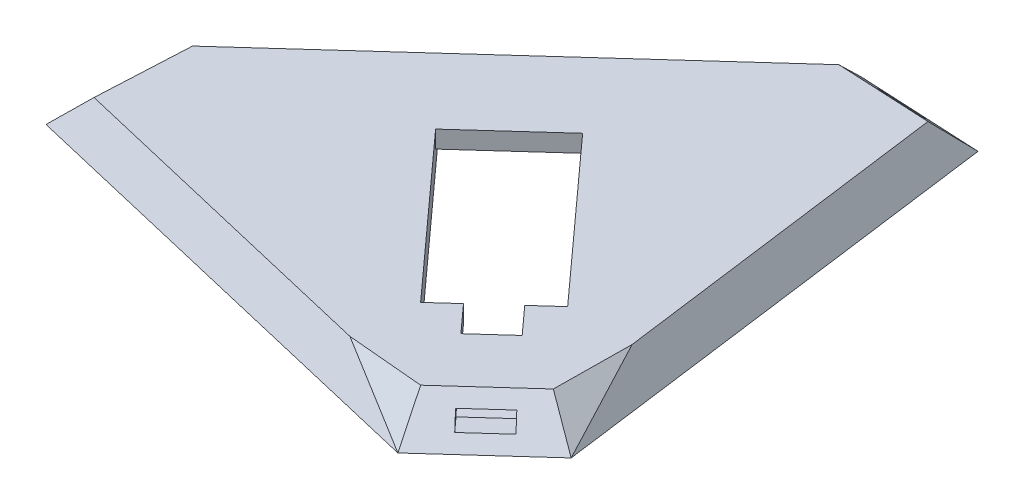
SolidWorks part; units mm, degrees
ref_plane "Front Plane" through (0, 0, 0) normal (0, 0, 1) x (1, 0, 0)
ref_plane "Top Plane" through (0, 0, 0) normal (0, 1, 0) x (1, 0, 0)
ref_plane "Right Plane" through (0, 0, 0) normal (1, 0, 0) x (0, 0, -1)
sketch "Sketch1" plane through (0, 0, 0) normal (0, 1, 0) x (1, 0, 0)
  line L20 (52.4944, -151.1339) -> (51.789, -165.2584)
  line L21 (51.789, -165.2584) -> (104.862, -177.7702)
  line L22 (104.862, -177.7702) -> (115.3483, -168.2814)
  line L23 (115.3483, -168.2814) -> (108.1862, -114.226)
  line L24 (108.1862, -114.226) -> (94.0617, -113.5206)
  line L25 (94.0617, -113.5206) -> (52.4944, -151.1339)
  line L26 (52.4944, -151.1339) -> (51.789, -165.2584) construction
  line L27 (108.1862, -114.226) -> (94.0617, -113.5206) construction
extrude "Boss-Extrude1" add sketch "Sketch1" along normal up to vertex (4 mm away)
draft "Draft1" type of draft neutral plane draft angle 45 faces to draft 4 face at (73.278, 2, 132.3272) face at (110.1052, 2, 173.0258) face at (52.1417, 2, 158.1961) face at (101.1239, 2, 113.8733) neutral plane through (0, 0, 0) neutral plane normal (0, -1, 0) reverse direction yes parameters "D1"=45
draft "Draft2" type of draft neutral plane draft angle 30.5 faces to draft 2 face at (78.1327, 2, 171.4689) face at (111.7413, 2, 141.0574) neutral plane through (0, 0, 0) neutral plane normal (0, -1, 0) reverse direction yes parameters "D1"=30.5
sketch "Sketch2" plane through (0, 0, 0) normal (0, -1, 0) x (1, 0, 0)
  line L0 (75.8497, 144.1117) -> (97.9914, 168.581)
  line L1 (97.9914, 168.581) -> (106.8893, 160.5295)
  line L2 (106.8893, 160.5295) -> (84.7477, 136.0602)
  line L3 (84.7477, 136.0602) -> (75.8497, 144.1117)
  line L4 (104.862, 177.7702) -> (115.3483, 168.2814) construction
  line L7 (73.278, 132.3272) -> (110.1052, 173.0258) construction
  line L8 (94.0617, 113.5206) -> (52.4944, 151.1339) construction
  point P6 (102.4404, 164.5553)
  point P11 (91.6916, 152.6765)
  dimension "D1" = 33
  dimension "D2" = 12
  dimension "D3" = 16.02
extrude "Cut-Extrude5" cut sketch "Sketch2" against normal blind 2
sketch "Sketch3" plane through (0, 2, 0) normal (0, -1, 0) x (1, 0, 0)
  line L0 (95.1398, 165.4297) -> (97.735, 163.0813)
  line L1 (97.9914, 168.581) -> (75.8497, 144.1117) construction
  line L2 (84.7477, 136.0602) -> (106.8893, 160.5295) construction
  line L3 (104.0377, 157.3782) -> (87.5992, 139.2116)
  line L5 (97.9914, 168.581) -> (75.8497, 144.1117) construction
  line L6 (78.7013, 147.2631) -> (95.1398, 165.4297)
  line L7 (106.8893, 160.5295) -> (97.9914, 168.581) construction
  line L8 (97.735, 163.0813) -> (100.5866, 166.2327)
  line L13 (78.7013, 147.2631) -> (87.5992, 139.2116)
  line L14 (100.5866, 166.2327) -> (104.2941, 162.8779)
  line L15 (104.2941, 162.8779) -> (101.4425, 159.7265)
  line L16 (101.4425, 159.7265) -> (104.0377, 157.3782)
  dimension "D1" = 24.5
  dimension "D2" = 4.25
  dimension "D4" = 5
extrude "Cut-Extrude6" cut sketch "Sketch3" against normal through all
sketch "Sketch5" plane through (67.8252, 101.0869, 74.9553) normal (0.4744, 0.7071, 0.5243) x (-0.5808, -0.1961, 0.7901)
  line L0 (79.5482, 125.8303) -> (76.3872, 120.8551)
  line L1 (77.8796, 120.4242) -> (64.4913, 124.2897) construction
  line L2 (76.3872, 120.8551) -> (79.5482, 125.8303) construction
  line L3 (65.9611, 129.7533) -> (65.9837, 123.8588)
  line L4 (77.8796, 120.4242) -> (64.4913, 124.2897) construction
  line L5 (65.9837, 123.8588) -> (71.4758, 142.8808) construction
sketch "Sketch9" plane through (0, 0, 0) normal (0, -1, 0) x (1, 0, 0)
  line L0 (52.1417, 158.1961) -> (114.4242, 161.3064)
  line L1 (52.4944, 151.1339) -> (51.789, 165.2584) construction
  line L2 (115.3483, 168.2814) -> (108.1862, 114.226) construction
  line L3 (101.1239, 113.8733) -> (98.0137, 176.1558)
  line L4 (108.1862, 114.226) -> (94.0617, 113.5206) construction
  line L5 (51.789, 165.2584) -> (104.862, 177.7702) construction
sketch "Sketch4" plane through (0, 4, 0) normal (0, 1, 0) x (1, 0, 0)
  line L0 (112.5878, -165.3849) -> (111.4359, -166.4272)
  line L1 (102.2549, -174.7349) -> (112.5878, -165.3849) construction
  line L2 (111.4359, -166.4272) -> (130.2228, -187.189) construction
  line L3 (111.4359, -166.4272) -> (111.5357, -157.4446)
  line L4 (112.5878, -165.3849) -> (106.3278, -118.1382) construction
  line L5 (111.5357, -157.4446) -> (112.5878, -165.3849)
sketch "Sketch7" plane through (67.8252, 101.0869, 74.9553) normal (0.4744, 0.7071, 0.5243) x (-0.5808, -0.1961, 0.7901)
  line L5 (74.0946, 123.4201) -> (69.2908, 124.8071)
  line L6 (69.2908, 124.8071) -> (69.8456, 126.7286)
  line L7 (69.8456, 126.7286) -> (74.6493, 125.3416)
  line L8 (74.6493, 125.3416) -> (74.0946, 123.4201)
  line L9 (77.8796, 120.4242) -> (64.4913, 124.2897) construction
  line L10 (71.1855, 122.3569) -> (72.7546, 127.7918) construction
  line L11 (79.5482, 125.8303) -> (65.9611, 129.7533) construction
  line L12 (78.7139, 123.1273) -> (65.2262, 127.0215) construction
  line L13 (77.8796, 120.4242) -> (79.5482, 125.8303) construction
  line L14 (64.4913, 124.2897) -> (65.9611, 129.7533) construction
  point P21 (72.2474, 126.0351)
  point P28 (71.9701, 125.0744)
  point P29 (71.9701, 125.0744)
  point P30 (69.5682, 125.7679)
  dimension "D1" = 2
  dimension "D2" = 5
extrude "Cut-Extrude9" cut sketch "Sketch7" along direction (-0.671, 0, -0.7415) on the side against the normal blind 2.2
extrude "Cut-Extrude7" cut sketch "Sketch4" along direction (-0.6637, 0.6786, -0.3146) on the side against the normal up to surface (5.8945 mm away)
sketch "Sketch6" plane through (0, 4, 0) normal (0, 1, 0) x (1, 0, 0)
  line L0 (102.2549, -174.7349) -> (103.4067, -173.6926)
  line L1 (103.4067, -173.6926) -> (94.4589, -172.897)
  line L2 (55.8669, -163.799) -> (102.2549, -174.7349) construction
  line L3 (94.4589, -172.897) -> (102.2549, -174.7349)
  line L4 (111.5357, -157.4446) -> (111.4359, -166.4272) construction
extrude "Cut-Extrude8" cut sketch "Sketch6" along direction (-0.2469, 0.6786, -0.6918) on the side against the normal up to surface (5.8945 mm away)
sketch "Sketch8" plane through (29.9461, -29.9835, 1.4954) normal (-0.7062, 0.7071, -0.0353) x (0.708, 0.7053, -0.0352)
  line L0 (31.8484, -150.9462) -> (30.8521, -165.0532) construction
  line L1 (34.9931, -160.7622) -> (35.3454, -155.7746)
  line L2 (34.9931, -160.7622) -> (32.9981, -160.6213)
  line L3 (32.9981, -160.6213) -> (33.3503, -155.6337)
  line L4 (35.3454, -155.7746) -> (33.3503, -155.6337)
  line L5 (34.9931, -160.7622) -> (33.3503, -155.6337) construction
  line L6 (32.9981, -160.6213) -> (35.3454, -155.7746) construction
  line L9 (36.9932, -158.3962) -> (31.3503, -157.9997) construction
  line L10 (37.3745, -152.9975) -> (36.6119, -163.7949) construction
  line L12 (34.6114, -151.9719) -> (33.732, -164.424) construction
  line L13 (37.3745, -152.9975) -> (31.8484, -150.9462) construction
  line L14 (36.6119, -163.7949) -> (30.8521, -165.0532) construction
  point P0 (34.1717, -158.1979)
  point P7 (33.9956, -160.6917)
  point P8 (31.3503, -157.9997)
  dimension "D1" = 2
  dimension "D2" = 5
extrude "Cut-Extrude10" cut sketch "Sketch8" along direction (0.9988, 0, 0.0499) on the side against the normal blind 2.2
ref_plane "Plane2" through (-25.5452, 0, 23.1152) normal (-0.7415, 0, 0.671) x (0.671, 0, 0.7415)
mirror "Mirror1" about plane through (-25.5452, 0, 23.1152) normal (-0.7415, 0, 0.671) of "Cut-Extrude10"
